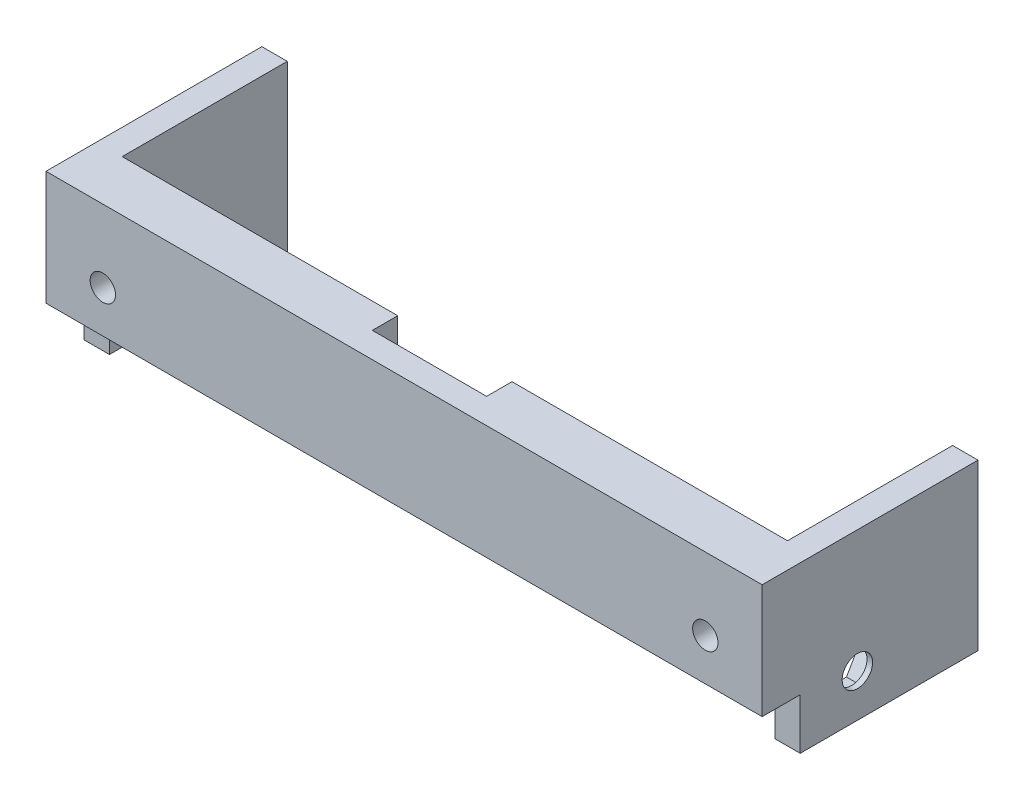
SolidWorks part; units mm, degrees
ref_plane "Piano frontale" through (0, 0, 0) normal (0, 0, 1) x (1, 0, 0)
ref_plane "Piano superiore" through (0, 0, 0) normal (0, 1, 0) x (1, 0, 0)
ref_plane "Piano destro" through (0, 0, 0) normal (1, 0, 0) x (0, 0, -1)
sketch "Schizzo1" plane through (0, 0, 0) normal (0, 0, 1) x (1, 0, 0)
  line L0 (-28.2, 0) -> (28.2, 0)
  line L1 (0, 0) -> (0, -48.4131) construction
  line L2 (-28.2, 0) -> (-28.2, -9)
  line L3 (-28.2, -9) -> (28.2, -9)
  line L4 (28.2, 0) -> (28.2, -9)
  circle A0 centre (-23.725, -5.7) radius 1
  circle A1 centre (23.725, -5.7) radius 1
  point P7 (0, -9)
  dimension "D4" = 2
  dimension "D1" = 56.4
  dimension "D2" = 9
  dimension "D3" = 3.3
  dimension "D5" = 47.45
extrude "Estrusione-Estrusione1" add sketch "Schizzo1" along normal blind 3
sketch "Schizzo3" plane through (28.2, 0, 0) normal (1, 0, 0) x (0, 0, -1)
  line L1 (0, 0) -> (14, 0)
  line L2 (0, 0) -> (0, -13)
  line L3 (0, -13) -> (14, -13)
  line L4 (14, 0) -> (14, -13)
  line L7 (14, -19.28) -> (14, -32.78) construction
  dimension "D1" = 13
extrude "Estrusione-Estrusione3" add sketch "Schizzo3" against normal blind 2
hole_wizard "Foro per Vite M2-1" positions "Schizzo5" profile "Schizzo4" hole size "M2" standard "Ansi Metric" end condition up to next
sketch "Schizzo5" plane through (28.2, 0, 0) normal (1, 0, 0) x (0, 0, -1)
  line L1 (0, 0) -> (0, -9) construction
  line L3 (0, -3.44) -> (9, -3.44) construction
  point P0 (4.5, -9.64)
  dimension "D1" = 4.5
  dimension "D2" = 6.2
sketch "Schizzo4" plane through (28.2, -9.64, -4.5) normal (0, 1, 0) x (0, 0, -1)
  line L0 (0, 0) -> (0, 56.4)
  line L1 (0, 56.4) -> (1.2, 56.4)
  line L2 (1.2, 56.4) -> (1.2, 0)
  line L5 (1.2, 0) -> (0, 0)
  line L11 (0, -6.35) -> (0, 107.95) construction
  dimension "Thru Hole Dia." = 2.4
  dimension "Thru Hole Depth" = 56.4
sketch "Schizzo6" plane through (26.2, 0, 0) normal (-1, 0, 0) x (0, 0, 1)
  line L1 (-3.3597, -7.665) -> (-5.6403, -7.665)
  line L2 (-5.6403, -7.665) -> (-6.7805, -9.64)
  line L3 (-6.7805, -9.64) -> (-5.6403, -11.615)
  line L4 (-5.6403, -11.615) -> (-3.3597, -11.615)
  line L5 (-3.3597, -11.615) -> (-2.2195, -9.64)
  line L6 (-2.2195, -9.64) -> (-3.3597, -7.665)
  circle A0 centre (-4.5, -9.64) radius 1.975 construction
  dimension "D1" = 3.95
extrude "Taglio-Estrusione1" cut sketch "Schizzo6" against normal blind 1.56
mirror "Specchia2" about plane through (0, 0, 0) normal (1, 0, 0) of "Taglio-Estrusione1", "Foro per Vite M2-1", "Estrusione-Estrusione3"
sketch "Schizzo8" plane through (0, 0, 0) normal (0, 0, 1) x (1, 0, 0)
  line L0 (5, -4.69) -> (13, -4.69) construction
  line L1 (13, -4.69) -> (13, -4.19) construction
  line L2 (13, -4.19) -> (5, -4.19) construction
  line L3 (5, -4.19) -> (5, -4.69) construction
  line L4 (5, -4.69) -> (13, -4.69) construction
  line L5 (13, -4.69) -> (13, -4.19) construction
  line L6 (13, -4.19) -> (5, -4.19) construction
  line L7 (5, -4.19) -> (5, -4.69) construction
  line L8 (4.5, -5.19) -> (13.5, -5.19)
  line L9 (13.5, -5.19) -> (13.5, -3.69)
  line L10 (13.5, -3.69) -> (4.5, -3.69)
  line L11 (4.5, -3.69) -> (4.5, -5.19)
  dimension "D1" = 0.5
extrude "Taglio-Estrusione2" cut sketch "Schizzo8" along normal blind 1
sketch "Schizzo2" plane through (0, 0, 0) normal (0, 0, -1) x (-1, 0, 0)
  line L1 (-26.2, 0) -> (26.2, 0)
  line L2 (-26.2, 0) -> (-26.2, -2)
  line L3 (-26.2, -2) -> (26.2, -2)
  line L4 (26.2, 0) -> (26.2, -2)
  line L5 (-26.2, 0) -> (26.2, 0) construction
  dimension "D1" = 2
extrude "Estrusione-Estrusione6" add sketch "Schizzo2" along normal blind 1
sketch "Schizzo9" plane through (0, 0, 0) normal (0, 1, 0) x (1, 0, 0)
  line L0 (-26.2, 1) -> (26.2, 1) construction
  line L1 (-4.5, -1) -> (4.5, -1)
  line L2 (-4.5, -1) -> (-4.5, 1)
  line L3 (-4.5, 1) -> (4.5, 1)
  line L4 (4.5, -1) -> (4.5, 1)
  line L5 (-4.5, -1) -> (4.5, 1) construction
  line L6 (-4.5, 1) -> (4.5, -1) construction
  point P0 (0, 0)
  dimension "D1" = 9
  dimension "D2" = 2
extrude "Taglio-Estrusione3" cut sketch "Schizzo9" against normal blind 2
extrude "Taglio-Estrusione5" cut sketch "Schizzo11" along normal through all from surface at -29.09 contours L2 L5 L4 L3
sketch "Schizzo11" plane through (0, -32.78, -9) normal (0, -1, 0) x (-1, 0, 0)
  line L0 (0, -9) -> (0, -12) construction
  line L1 (8.5, -10) -> (8.5, -10.6)
  line L2 (-8.5, -10) -> (-21.5, -10)
  line L3 (-8.5, -10) -> (-8.5, -10.6)
  line L4 (-8.5, -10.6) -> (-21.5, -10.6)
  line L5 (-21.5, -10) -> (-21.5, -10.6)
  line L6 (8.5, -10.6) -> (21.5, -10.6)
  line L7 (21.5, -10) -> (21.5, -10.6)
  line L16 (-28.2, -9) -> (-28.2, -12) construction
  line L19 (26.2, -9) -> (-26.2, -9) construction
  line L22 (28.2, -12) -> (28.2, -9) construction
  line L23 (-28.2, -12) -> (28.2, -12) construction
  line L24 (8.5, -10) -> (21.5, -10)
  line L26 (-20, -10) -> (-10, -10)
  line L28 (-15, -10) -> (-15, -10.6) construction
  line L361 (-26.2, -9) -> (-28.2, -9)
  line L363 (28.2, -9) -> (26.2, -9)
